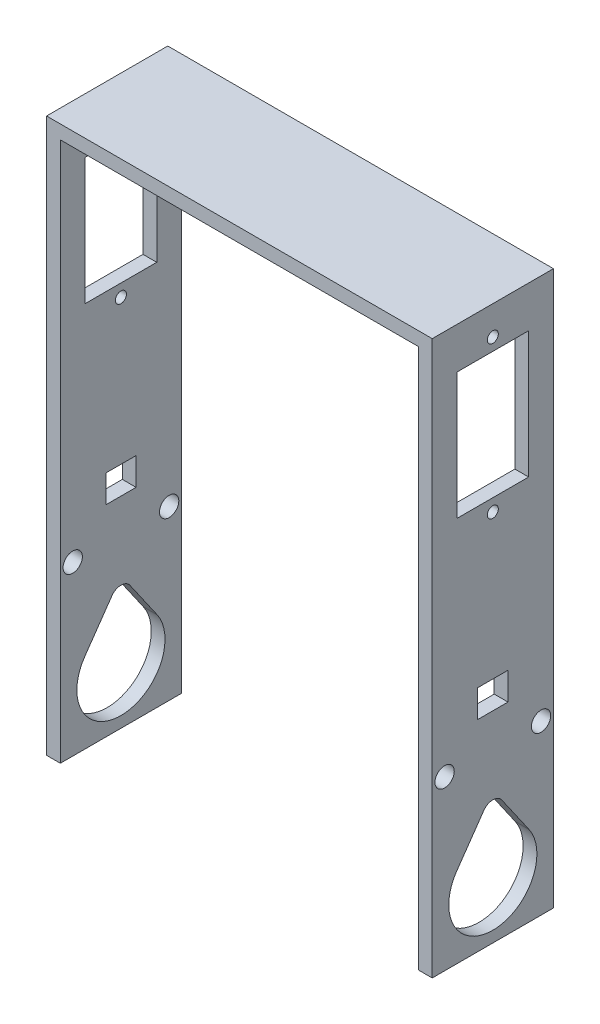
SolidWorks part; units mm, degrees
ref_plane "Alzado" through (0, 0, 0) normal (0, 0, 1) x (1, 0, 0)
ref_plane "Planta" through (0, 0, 0) normal (0, 1, 0) x (1, 0, 0)
ref_plane "Vista lateral" through (0, 0, 0) normal (1, 0, 0) x (0, 0, -1)
sketch "Croquis1" plane through (0, 0, 0) normal (1, 0, 0) x (0, 0, -1)
  line L0 (0, 0) -> (0, 10.5) construction
  line L1 (-6.5652, 4.5714) -> (-1.6413, 11.6429)
  line L2 (0, 0) -> (0, -10) construction
  line L3 (1.6413, 11.6429) -> (6.5652, 4.5714)
  line L4 (-11, -10) -> (11, -10)
  line L5 (-11, -10) -> (-11, 90.5)
  line L6 (-11, 90.5) -> (11, 90.5)
  line L7 (11, -10) -> (11, 90.5)
  line L8 (0, 0) -> (8, 0) construction
  line L9 (-8.75, 20.5) -> (8.75, 20.5) construction
  line L10 (0, 20.5) -> (0, 10.5) construction
  line L11 (-11, 55.5) -> (11, 55.5) construction
  line L12 (0, 90.5) -> (0, 83) construction
  line L13 (-6.5, 83) -> (6.5, 83)
  line L14 (-6.5, 83) -> (-6.5, 60)
  line L15 (-6.5, 60) -> (6.5, 60)
  line L16 (6.5, 83) -> (6.5, 60)
  line L17 (0, 60) -> (0, 55.5) construction
  line L18 (0, 20.5) -> (0, 26.5) construction
  line L19 (-2.75, 31.5) -> (2.75, 31.5)
  line L20 (-2.75, 31.5) -> (-2.75, 26.5)
  line L21 (-2.75, 26.5) -> (2.75, 26.5)
  line L22 (2.75, 31.5) -> (2.75, 26.5)
  arc A0 (-6.5652, 4.5714) -> (6.5652, 4.5714) centre (0, 0) ccw
  arc A1 (1.6413, 11.6429) -> (-1.6413, 11.6429) centre (0, 10.5) ccw
  circle A2 centre (-8.75, 20.5) radius 1.75
  circle A3 centre (8.75, 20.5) radius 1.75
  circle A4 centre (0, 85.25) radius 1
  circle A5 centre (0, 57.75) radius 1
  dimension "D2" = 4
  dimension "D3" = 16
  dimension "D9" = 3.5
  dimension "D14" = 2
  dimension "D1" = 10.5
  dimension "D4" = 22
  dimension "D5" = 10
  dimension "D6" = 3
  dimension "D7" = 17.5
  dimension "D8" = 20.5
  dimension "D10" = 35
  dimension "D11" = 13
  dimension "D12" = 23
  dimension "D13" = 27.5
  dimension "D15" = 2.25
  dimension "D16" = 2.25
  dimension "D17" = 35
  dimension "D18" = 4.5
  dimension "D19" = 7.5
  dimension "D20" = 100.5
  dimension "D21" = 5.5
  dimension "D22" = 5
  dimension "D23" = 6
extrude "Saliente-Extruir1" add sketch "Croquis1" along normal mid plane 70
sketch "Croquis2" plane through (0, 0, 11) normal (0, 0, 1) x (1, 0, 0)
  line L13 (32.5, -10) -> (32.5, 88)
  line L14 (32.5, 88) -> (-32.5, 88)
  line L15 (-32.5, 88) -> (-32.5, -10)
  line L16 (32.5, -10) -> (32.5, 88)
  line L17 (32.5, 88) -> (-32.5, 88)
  line L18 (-32.5, 88) -> (-32.5, -10)
  dimension "D1" = 2.5
extrude "Cortar-Extruir2" cut sketch "Croquis2" against normal through all and the other way through all
